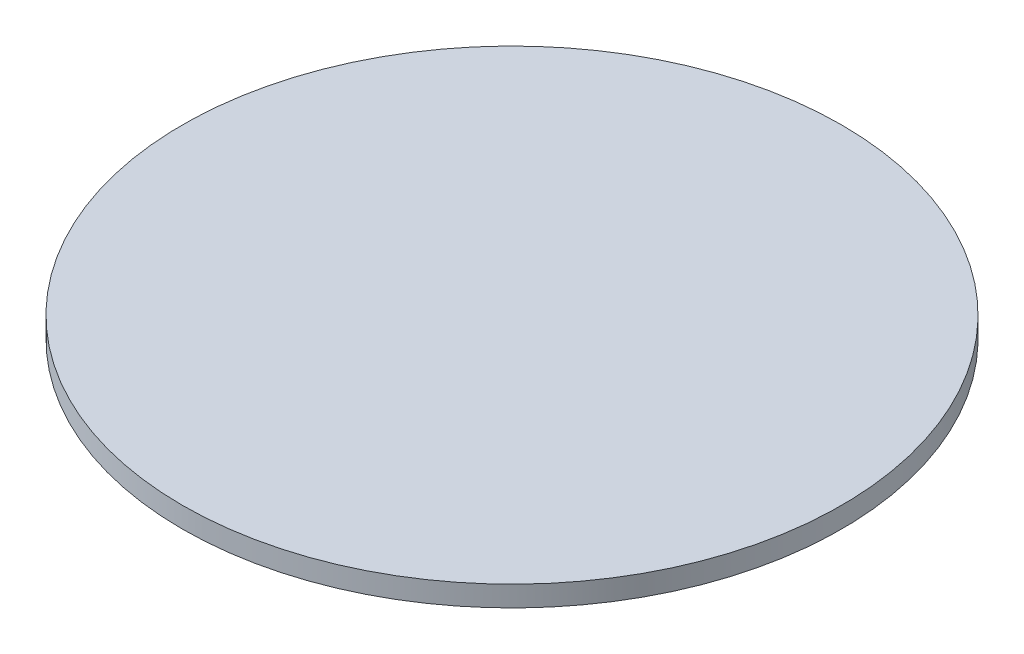
SolidWorks part; units mm, degrees
ref_plane "Front Plane" through (0, 0, 0) normal (0, 0, 1) x (1, 0, 0)
ref_plane "Top Plane" through (0, 0, 0) normal (0, 1, 0) x (1, 0, 0)
ref_plane "Right Plane" through (0, 0, 0) normal (1, 0, 0) x (0, 0, -1)
sketch "Sketch1" plane through (0, 0, 0) normal (0, 1, 0) x (1, 0, 0)
  circle A0 centre (0, 0) radius 130
  dimension "D1" = 260
extrude "Boss-Extrude1" add sketch "Sketch1" against normal blind 20
sketch "Sketch2" plane through (0, 0, 0) normal (0, 1, 0) x (1, 0, 0)
  circle A0 centre (0, 0) radius 160
  point P2 (0, 0)
  dimension "D1" = 320
extrude "Boss-Extrude2" add sketch "Sketch2" along normal blind 10
